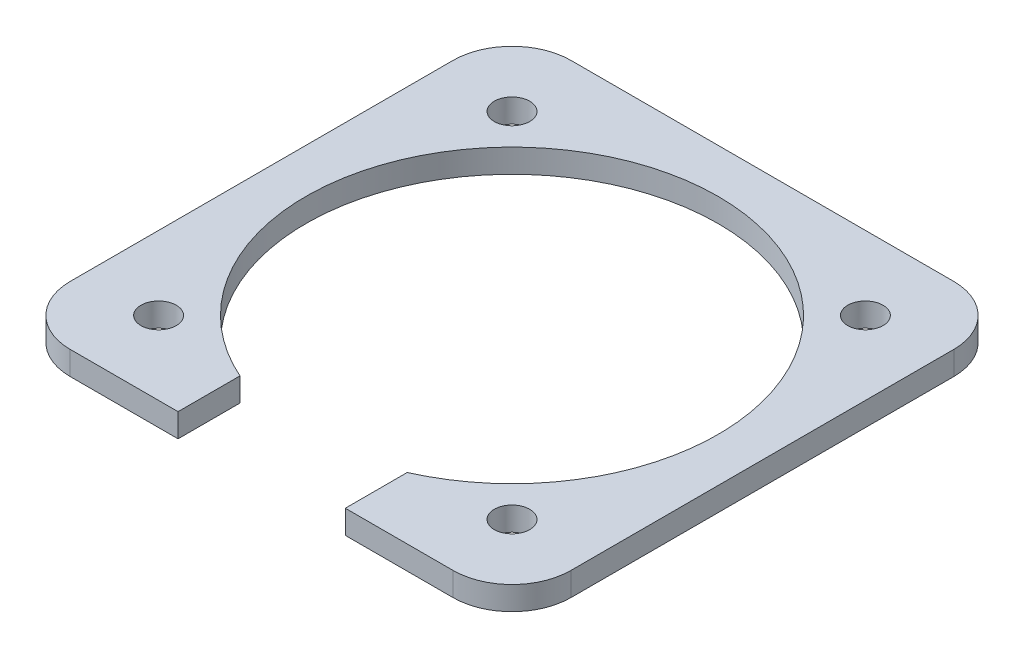
SolidWorks part; units mm, degrees
ref_plane "Front Plane" through (0, 0, 0) normal (0, 0, 1) x (1, 0, 0)
ref_plane "Top Plane" through (0, 0, 0) normal (0, 1, 0) x (1, 0, 0)
ref_plane "Right Plane" through (0, 0, 0) normal (1, 0, 0) x (0, 0, -1)
sketch "Sketch1" plane through (0, 0, 0) normal (0, 1, 0) x (1, 0, 0)
  line L1 (-20.25, -20.25) -> (20.25, -20.25)
  line L2 (-20.25, -20.25) -> (-20.25, 20.25)
  line L3 (-20.25, 20.25) -> (20.25, 20.25)
  line L4 (20.25, -20.25) -> (20.25, 20.25)
  line L5 (-20.25, -20.25) -> (20.25, 20.25) construction
  line L6 (-20.25, 20.25) -> (20.25, -20.25) construction
  circle A0 centre (0, 0) radius 17.5
extrude "Boss-Extrude1" add sketch "Sketch1" along normal blind 2
sketch "Sketch2" plane through (0, 2, 0) normal (0, 1, 0) x (1, 0, 0)
  circle A0 centre (-15, 15) radius 1.25
  circle A1 centre (15, 15) radius 1.25
  circle A2 centre (-15, -15) radius 1.25
  circle A3 centre (15, -16.25) radius 1.25
extrude "Cut-Extrude1" cut sketch "Sketch2" against normal blind 2
sketch "Sketch3" plane through (0, 2, 0) normal (0, 1, 0) x (1, 0, 0)
  line L0 (0, -20.25) -> (7.1, -20.25)
  line L1 (-20.25, -20.25) -> (20.25, -20.25) construction
  line L2 (0, -20.25) -> (-7.1, -20.25)
  line L3 (-7.1, -20.25) -> (-7.1, -15.995)
  line L4 (-7.1, -15.995) -> (7.1, -15.995)
  line L5 (7.1, -15.995) -> (7.1, -20.25)
  circle A0 centre (0, 0) radius 17.5 construction
extrude "Cut-Extrude2" cut sketch "Sketch3" against normal blind 2
sketch "Sketch4" plane through (0, 2, 0) normal (0, 1, 0) x (1, 0, 0)
  line L1 (20.25, -20.25) -> (-20.25, -20.25)
  line L2 (20.25, -20.25) -> (20.25, 20.25)
  line L3 (20.25, 20.25) -> (-20.25, 20.25)
  line L4 (-20.25, -20.25) -> (-20.25, 20.25)
  line L5 (20.25, -20.25) -> (-20.25, 20.25) construction
  line L6 (20.25, 20.25) -> (-20.25, -20.25) construction
  line L7 (21.25, -21.25) -> (-21.25, -21.25)
  line L8 (21.25, -21.25) -> (21.25, 21.25)
  line L9 (21.25, 21.25) -> (-21.25, 21.25)
  line L10 (-21.25, -21.25) -> (-21.25, 21.25)
  line L11 (21.25, -21.25) -> (-21.25, 21.25) construction
  line L12 (21.25, 21.25) -> (-21.25, -21.25) construction
  point P0 (0, 0)
  point P7 (0, 0)
extrude "Boss-Extrude2" add sketch "Sketch4" against normal blind 2
sketch "Sketch5" plane through (0, 2, 0) normal (0, 1, 0) x (1, 0, 0)
  line L0 (-21.25, -21.25) -> (21.25, -21.25) construction
  line L1 (-7.1, -22.25) -> (7.1, -22.25)
  line L2 (-7.1, -22.25) -> (-7.1, -20.25)
  line L3 (-7.1, -20.25) -> (7.1, -20.25)
  line L4 (7.1, -22.25) -> (7.1, -20.25)
  line L5 (-7.1, -22.25) -> (7.1, -20.25) construction
  line L6 (-7.1, -20.25) -> (7.1, -22.25) construction
  point P0 (0, -21.25)
extrude "Cut-Extrude3" cut sketch "Sketch5" against normal blind 2
sketch "Sketch6" plane through (0, 2, 0) normal (0, 1, 0) x (1, 0, 0)
  circle A0 centre (-15, 15) radius 1.5
  circle A1 centre (15, 15) radius 1.5
  circle A2 centre (15, -16.25) radius 1.5
  circle A3 centre (-15, -15) radius 1.5
extrude "Cut-Extrude4" cut sketch "Sketch6" against normal blind 3.5
sketch "Sketch7" plane through (0, 2, 0) normal (0, 1, 0) x (1, 0, 0)
  circle A0 centre (15, -16.25) radius 1.5
extrude "Boss-Extrude3" add sketch "Sketch7" against normal blind 2
sketch "Sketch8" plane through (0, 2, 0) normal (0, 1, 0) x (1, 0, 0)
  circle A0 centre (15, -15) radius 1.5
extrude "Cut-Extrude5" cut sketch "Sketch8" against normal blind 2
fillet "Fillet2" radius 5 4 edges at (-21.25, 1, 21.25) (21.25, 1, 21.25) (21.25, 1, -21.25) (-21.25, 1, -21.25)
